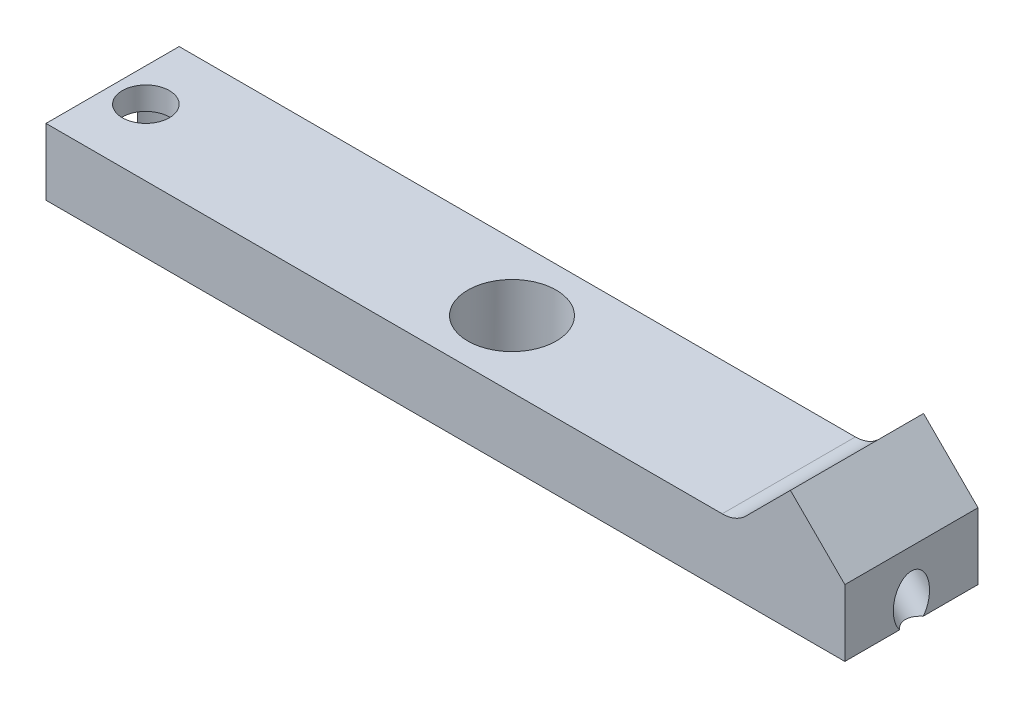
SolidWorks part; units mm, degrees
ref_plane "Front" through (0, 0, 0) normal (0, 0, 1) x (1, 0, 0)
ref_plane "Top" through (0, 0, 0) normal (0, 1, 0) x (1, 0, 0)
ref_plane "Right" through (0, 0, 0) normal (1, 0, 0) x (0, 0, -1)
sketch "Sketch1" plane through (0, 0, 0) normal (0, 1, 0) x (1, 0, 0)
  line L1 (-38.1, -6.35) -> (38.1, -6.35)
  line L2 (-38.1, -6.35) -> (-38.1, 6.35)
  line L3 (-38.1, 6.35) -> (38.1, 6.35)
  line L4 (38.1, -6.35) -> (38.1, 6.35)
  line L5 (-38.1, -6.35) -> (38.1, 6.35) construction
  line L6 (-38.1, 6.35) -> (38.1, -6.35) construction
  point P0 (0, 0)
  dimension "D1" = 76.2
  dimension "D2" = 12.7
extrude "Boss-Extrude1" add sketch "Sketch1" along normal mid plane 6.35 contours L3 L4 L1 L2
sketch "Sketch2" plane through (0, 3.175, 0) normal (0, 1, 0) x (1, 0, 0)
  point P0 (0, 0)
hole_wizard "5/16 Clearance Hole1" positions "Sketch3" profile "Sketch5" hole size "5/16" standard "ANSI Inch"
sketch "Sketch3" plane through (0, 3.175, 0) normal (0, 1, 0) x (1, 0, 0)
  point P0 (0, 0)
sketch "Sketch5" plane through (0, 3.175, 0) normal (1, 0, 0) x (0, 0, 1)
  line L0 (0, 0) -> (0, 19.0435)
  line L1 (0, 19.0435) -> (4.2164, 16.51)
  line L2 (4.2164, 16.51) -> (4.2164, 0)
  line L5 (4.2164, 0) -> (0, 0)
  line L10 (0, 19.0435) -> (-4.2164, 16.51) construction
  line L11 (0, -6.35) -> (0, 107.95) construction
  dimension "Hole Dia." = 8.4328
  dimension "Hole Depth" = 16.51
  dimension "Drill Angle" = 118
sketch "Sketch6" plane through (0, 0, 0) normal (0, 0, 1) x (1, 0, 0)
  line L0 (38.1, 3.175) -> (32.9078, 8.3672)
  line L1 (32.9078, 8.3672) -> (27.7157, 3.175)
  line L2 (-38.1, 3.175) -> (38.1, 3.175) construction
  line L3 (27.7157, 3.175) -> (38.1, 3.175)
  dimension "D1" = 7.3428
extrude "Boss-Extrude2" add sketch "Sketch6" along normal mid plane 12.7
sketch "Sketch7" plane through (0, -3.175, 0) normal (0, -1, 0) x (1, 0, 0)
  line L0 (50, 0) -> (-50, 0) construction
  line L1 (-38.1, 6.35) -> (-38.1, -6.35) construction
  point P0 (-34.925, 0)
  dimension "D1" = 3.175
hole_wizard "CBORE for #8 Socket Head Cap Screw1" positions "Sketch8" profile "Sketch10" counterbore size "#8" standard "ANSI Inch"
sketch "Sketch8" plane through (0, -3.175, 0) normal (0, -1, 0) x (-1, 0, 0)
  point P0 (34.925, 0)
sketch "Sketch10" plane through (-34.925, -3.175, 0) normal (1, 0, 0) x (0, 0, -1)
  line L0 (0, 0) -> (0, 17.8607)
  line L1 (0, 17.8607) -> (2.2479, 16.51)
  line L2 (2.2479, 16.51) -> (2.2479, 4.1656)
  line L3 (2.2479, 4.1656) -> (3.9688, 4.1656)
  line L4 (3.9688, 4.1656) -> (3.9688, 0)
  line L5 (3.9688, 0) -> (0, 0)
  line L10 (0, 17.8607) -> (-2.2479, 16.51) construction
  line L11 (0, -6.35) -> (0, 107.95) construction
  dimension "Hole Dia." = 4.4958
  dimension "Hole Depth" = 16.51
  dimension "C'Bore Dia." = 7.9375
  dimension "C'Bore Depth" = 4.1656
  dimension "Drill Angle" = 118
sketch "Sketch11" plane through (12.2703, -12.2703, 0) normal (-0.7071, 0.7071, 0) x (0, 0, 1)
  point P0 (0, 26.0108)
hole_wizard "#8-32 Tapped Hole1" positions "Sketch12" profile "Sketch13" tap size "#8-32" standard "ANSI Inch" end condition up to next
sketch "Sketch12" plane through (12.2703, -12.2703, 0) normal (-0.7071, 0.7071, 0) x (0.7071, 0.7071, 0)
  point P0 (26.0108, 0)
sketch "Sketch13" plane through (30.6628, 6.1221, 0) normal (0, 0, 1) x (-0.7071, -0.7071, 0)
  line L0 (0, 0) -> (0, 10.5178)
  line L1 (0, 10.5178) -> (1.7272, 10.5178)
  line L2 (1.7272, 10.5178) -> (1.7272, 0)
  line L5 (1.7272, 0) -> (0, 0)
  line L11 (0, -6.35) -> (0, 107.95) construction
  dimension "Thru Tap Drill Dia." = 3.4544
  dimension "Thru Tap Drill Depth" = 10.5178
cosmetic thread "Hole Thread1" parameters "D2"=4.1656
fillet "Fillet1" radius 3.175 1 edges at (27.7157, 3.175, 0)
